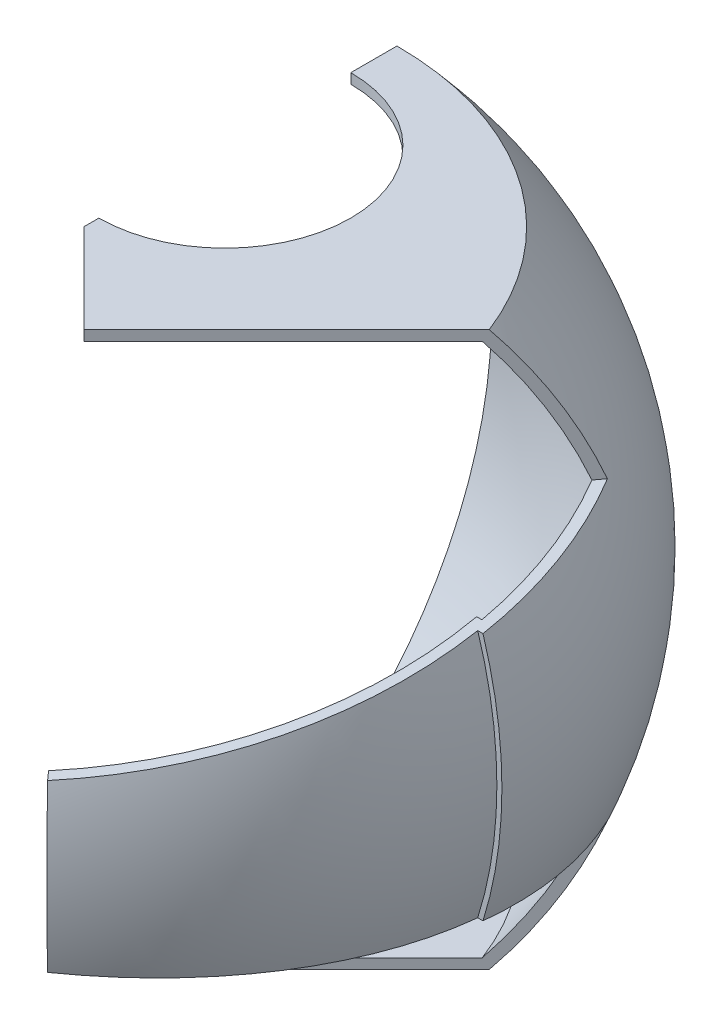
SolidWorks part; units mm, degrees
material "Ti-8Mn annealed sheet (SS)"
ref_plane "Front Plane" through (0, 0, 0) normal (0, 0, 1) x (1, 0, 0)
ref_plane "Top Plane" through (0, 0, 0) normal (0, 1, 0) x (1, 0, 0)
ref_plane "Right Plane" through (0, 0, 0) normal (1, 0, 0) x (0, 0, -1)
sketch "Sketch1" plane through (0, 0, 0) normal (1, 0, 0) x (0, 0, -1)
  line L0 (0, 0) -> (-61.7614, 0) construction
  line L1 (0, -55) -> (0, 55)
  line L2 (0, 55) -> (-76.6015, 55)
  line L3 (0, -55) -> (-76.6015, -55)
  arc A0 (-76.6015, 55) -> (-76.6015, -55) centre (0, 0) ccw
  point P5 (-30.8807, 0)
  dimension "D1" = 55
revolve "Revolve1" add sketch "Sketch1" angle 180 about L1
sketch "Sketch2" plane through (0, -55, 0) normal (0, -1, 0) x (1, 0, 0)
  line L4 (0, 0) -> (17.6777, 17.6777)
  line L5 (17.6777, 17.6777) -> (110.9753, -75.6199)
  line L10 (0, 0) -> (-110.1278, 0)
  line L11 (-110.1278, 0) -> (-110.1278, 155.9515)
  line L12 (-110.1278, 155.9515) -> (110.9753, 155.9515)
  line L13 (110.9753, 155.9515) -> (110.9753, -75.6199)
extrude "Cut-Extrude1" cut sketch "Sketch2" against normal through all
ref_plane "Plane1" through (100, 0, 0) normal (1, 0, 0) x (0, 0, -1)
sketch "Sketch3" plane through (100, 0, 0) normal (1, 0, 0) x (0, 0, -1)
  line L0 (-71.226, -15) -> (-71.226, 15)
  line L1 (39.0117, -30) -> (39.0117, 30)
  line L2 (-71.226, 15) -> (39.0117, 30)
  line L3 (-71.226, -15) -> (39.0117, -30)
extrude "Boss-Extrude1" add sketch "Sketch3" against normal up to surface (100 mm away)
sketch "Sketch4" plane through (0, 0, 0) normal (1, 0, 0) x (0, 0, -1)
  line L0 (-59.3612, 58.0108) -> (-134.5056, 58.0108)
  line L1 (-59.3612, -58.0108) -> (-134.5056, -58.0108)
  line L2 (0, 0) -> (0, 111.2084)
  arc A0 (-59.3612, 58.0108) -> (-59.3612, -58.0108) centre (0, 0) ccw
  arc A1 (-134.5056, 58.0108) -> (-134.5056, -58.0108) centre (0, 0) ccw
revolve "Cut-Revolve1" cut sketch "Sketch4" angle 360 about L2
sketch "Sketch5" plane through (0, -55, 0) normal (0, -1, 0) x (1, 0, 0)
  line L0 (0, 0) -> (70.4701, 80)
  line L1 (70.4701, 80) -> (-50.338, 80)
  line L2 (-50.338, 80) -> (-50.338, 0)
  line L3 (-50.338, 0) -> (0, 0)
extrude "Cut-Extrude2" cut sketch "Sketch5" against normal through all
sketch "Sketch6" plane through (0, 0, 0) normal (1, 0, 0) x (0, 0, -1)
  line L0 (-48.9855, 65.7603) -> (-101.4376, 65.7603)
  line L1 (-48.9855, -65.7603) -> (-101.4376, -65.7603)
  line L2 (0, 0) -> (0, 107.2889)
  arc A0 (-48.9855, 65.7603) -> (-48.9855, -65.7603) centre (0, 0) ccw
  arc A1 (-101.4376, 65.7603) -> (-101.4376, -65.7603) centre (0, 0) ccw
revolve "Cut-Revolve2" cut sketch "Sketch6" angle 90 about L2
sketch "Sketch7" plane through (0, -55, 0) normal (0, -1, 0) x (1, 0, 0)
  line L1 (0, -62.1611) -> (0, 0) construction
  circle A0 centre (0, -28) radius 25
extrude "Cut-Extrude3" cut sketch "Sketch7" against normal through all
shell "Shell1" thickness 2
